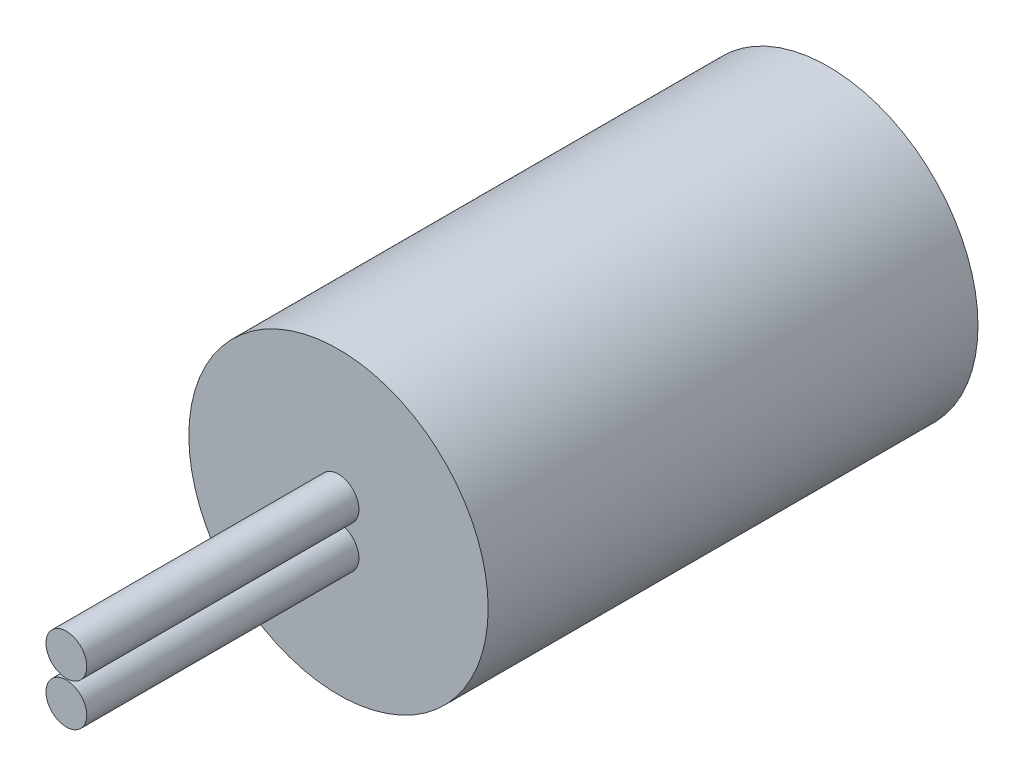
SolidWorks part; units mm, degrees
ref_plane "Front" through (0, 0, 0) normal (0, 0, 1) x (1, 0, 0)
ref_plane "Top" through (0, 0, 0) normal (0, 1, 0) x (1, 0, 0)
ref_plane "Right" through (0, 0, 0) normal (1, 0, 0) x (0, 0, -1)
sketch "Эскиз1" plane through (0, 0, 0) normal (0, 0, 1) x (1, 0, 0)
  circle A0 centre (0, 0) radius 5.5
  dimension "D1" = 11
extrude "Фара" add sketch "Эскиз1" along normal mid plane 18
sketch "Эскиз2" plane through (0, 0, 9) normal (0, 0, 1) x (1, 0, 0)
  line L0 (0, 0.775) -> (0, -0.775) construction
  circle A0 centre (0, -0.775) radius 0.75
  circle A1 centre (0, 0.775) radius 0.75
  point P5 (0, 0)
  dimension "D1" = 1.5
  dimension "D2" = 1.55
extrude "Провода" add sketch "Эскиз2" along normal blind 10
